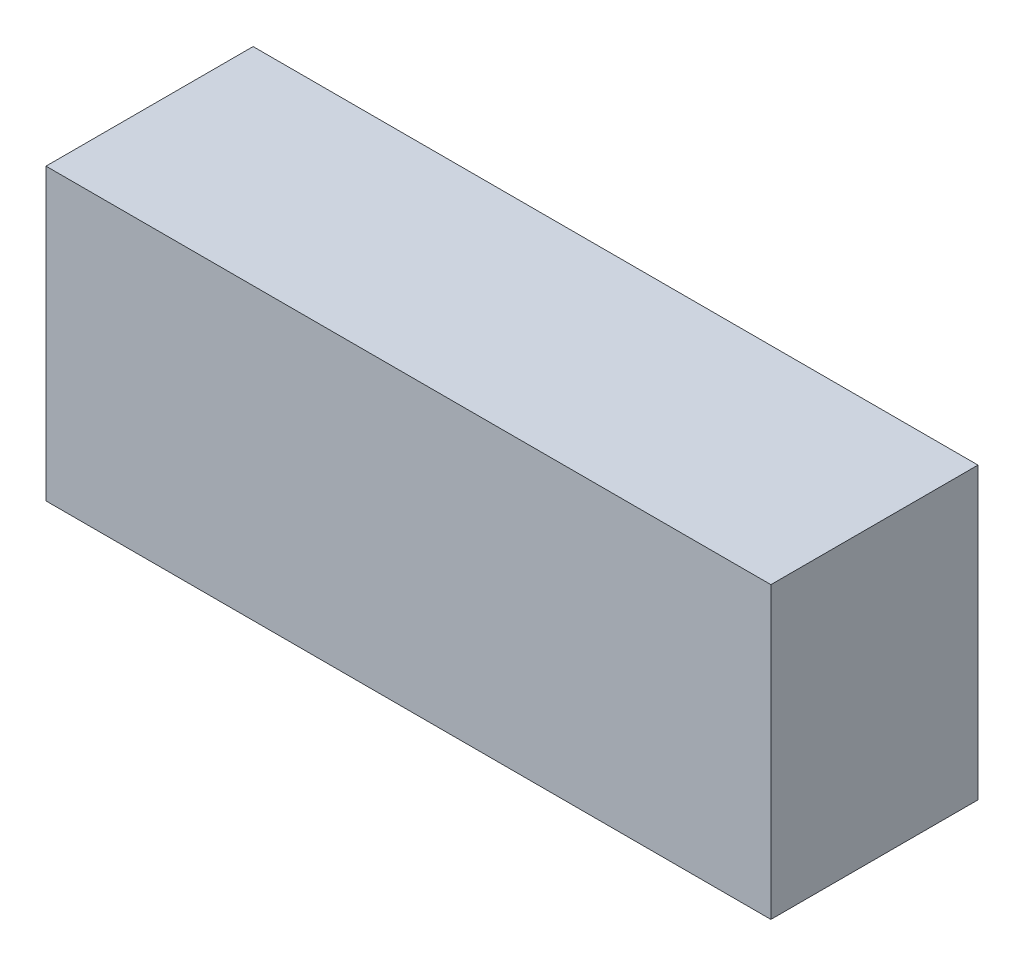
SolidWorks part; units mm, degrees
ref_plane "Front Plane" through (0, 0, 0) normal (0, 0, 1) x (1, 0, 0)
ref_plane "Top Plane" through (0, 0, 0) normal (0, 1, 0) x (1, 0, 0)
ref_plane "Right Plane" through (0, 0, 0) normal (1, 0, 0) x (0, 0, -1)
sketch "Sketch1" plane through (0, 0, 0) normal (0, 0, 1) x (1, 0, 0)
  line L1 (-35, -14) -> (35, -14)
  line L2 (-35, -14) -> (-35, 14)
  line L3 (-35, 14) -> (35, 14)
  line L4 (35, -14) -> (35, 14)
extrude "REFERENCE_ENVELOPE_NOT_MANUFACTURING" add sketch "Sketch1" along normal blind 20 from offset 0
